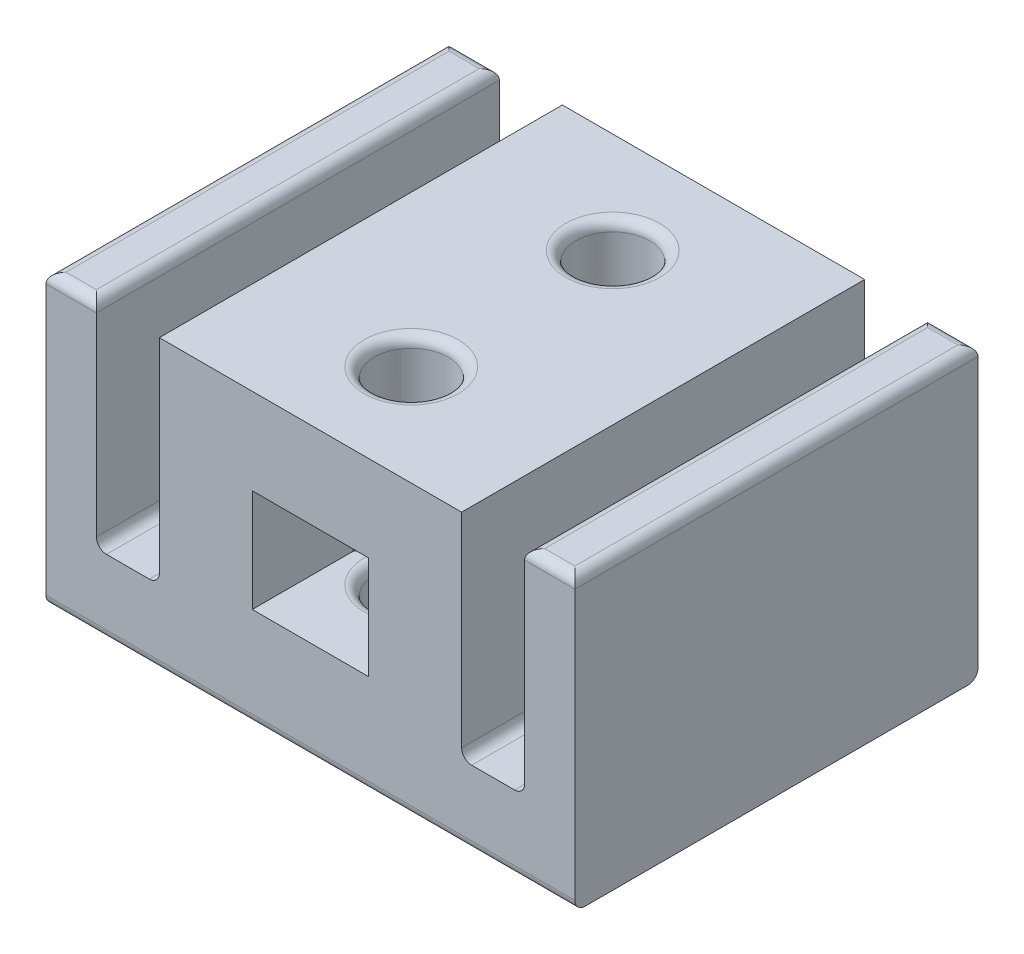
SolidWorks part; units mm, degrees
ref_plane "Front Plane" through (0, 0, 0) normal (0, 0, 1) x (1, 0, 0)
ref_plane "Top Plane" through (0, 0, 0) normal (0, 1, 0) x (1, 0, 0)
ref_plane "Right Plane" through (0, 0, 0) normal (1, 0, 0) x (0, 0, -1)
sketch "Sketch1" plane through (0, 0, 0) normal (0, 0, 1) x (1, 0, 0)
  line L0 (0, -18.7591) -> (0, 18.7591) construction
  line L1 (-12.7, 18.7591) -> (12.7, 18.7591) construction
  line L2 (12.7, 18.7591) -> (12.7, 6.8529) construction
  line L3 (-12.7, 18.7591) -> (-12.7, 6.8529) construction
  point P5 (0, 0)
  dimension "D1" = 12.7
  dimension "D2" = 11.9062
sketch "Sketch2" plane through (0, 0, 0) normal (0, 0, 1) x (1, 0, 0)
  line L0 (-12.7, 18.7591) -> (12.7, 18.7591) construction
  line L1 (-9.525, 18.7591) -> (9.525, 18.7591)
  line L2 (-9.525, 18.7591) -> (-9.525, 5.2654)
  line L3 (-9.525, 5.2654) -> (9.525, 5.2654) construction
  line L4 (9.525, 18.7591) -> (9.525, 5.2654)
  line L5 (12.7, 18.7591) -> (12.7, 6.8529) construction
  line L6 (9.525, 5.2654) -> (13.4938, 5.2654)
  line L7 (13.4938, 18.7591) -> (13.4938, 5.2654)
  line L8 (13.4938, 18.7591) -> (16.6688, 18.7591)
  line L9 (16.6688, 18.7591) -> (16.6688, 0.5029)
  line L10 (16.6688, 0.5029) -> (-16.6687, 0.5029)
  line L11 (-16.6687, 0.5029) -> (-16.6687, 18.7591)
  line L12 (-16.6687, 18.7591) -> (-13.4937, 18.7591)
  line L13 (-13.4937, 18.7591) -> (-13.4937, 5.2654)
  line L14 (-13.4937, 5.2654) -> (-9.525, 5.2654)
  line L15 (-12.7, 18.7591) -> (-12.7, 6.8529) construction
  point P20 (0, 0)
  point P23 (15.8316, 17.4334)
  dimension "D1" = 3.175
  dimension "D2" = 3.175
  dimension "D3" = 1.5875
  dimension "D4" = 0.7937
  dimension "D5" = 0.7937
  dimension "D6" = 3.175
  dimension "D7" = 4.7625
extrude "Boss-Extrude1" add sketch "Sketch2" along normal mid plane 25.4
sketch "Sketch4" plane through (0, 0.5029, 0) normal (0, -1, 0) x (1, 0, 0)
  line L0 (0, 0) -> (0, 6.35) construction
  circle A0 centre (0, 6.35) radius 2.3241
  circle A1 centre (0, -6.35) radius 2.3241
  point P6 (0, 0)
  dimension "D3" = 4.6482
  dimension "D1" = 6.35
  dimension "D2" = 6.35
extrude "Cut-Extrude1" cut sketch "Sketch4" against normal blind 19.05
sketch "Sketch5" plane through (0, 0.5029, 0) normal (0, -1, 0) x (1, 0, 0)
  line L0 (-3.6662, -6.35) -> (-3.6662, -14.1774)
  line L1 (1.8331, 9.525) -> (-1.8331, 9.525) construction
  line L2 (-1.8331, 9.525) -> (-3.6662, 6.35) construction
  line L3 (-3.6662, 6.35) -> (-1.8331, 3.175)
  line L4 (-1.8331, 3.175) -> (1.8331, 3.175)
  line L5 (1.8331, 3.175) -> (3.6662, 6.35)
  line L6 (3.6662, 6.35) -> (1.8331, 9.525) construction
  line L7 (3.6662, -6.35) -> (1.8331, -3.175)
  line L8 (1.8331, -3.175) -> (-1.8331, -3.175)
  line L9 (-1.8331, -3.175) -> (-3.6662, -6.35)
  line L10 (-3.6662, -6.35) -> (-1.8331, -9.525) construction
  line L11 (-1.8331, -9.525) -> (1.8331, -9.525) construction
  line L12 (1.8331, -9.525) -> (3.6662, -6.35) construction
  line L13 (-3.6662, -14.1774) -> (3.6662, -14.1774)
  line L14 (3.6662, -14.1774) -> (3.6662, -6.35)
  line L15 (3.6662, 6.35) -> (3.6662, 14.5068)
  line L16 (3.6662, 14.5068) -> (-3.6662, 14.5068)
  line L17 (-3.6662, 14.5068) -> (-3.6662, 6.35)
  circle A0 centre (0, 6.35) radius 3.175 construction
  circle A1 centre (0, -6.35) radius 3.175 construction
  dimension "D1" = 6.35
extrude "Cut-Extrude2" cut sketch "Sketch5" against normal blind 6.477 from offset 6.35 offset against normal yes
fillet "Fillet1" radius 0.635 22 edges at (2.3241, 0.5029, -6.35) (2.3241, 6.8529, -6.35) (2.3241, 0.5029, 6.35) (2.3241, 6.8529, 6.35) (2.3241, 13.3299, 6.35) (0, 18.7591, 4.0259) (2.3241, 13.3299, -6.35) (0, 18.7591, -8.6741) (16.6688, 18.7591, 0) (15.0813, 18.7591, 12.7) (13.4938, 18.7591, 0) (15.0813, 18.7591, -12.7) (-13.4937, 18.7591, 0) (-15.0812, 18.7591, 12.7) (-16.6687, 18.7591, 0) (-15.0812, 18.7591, -12.7) (0, 0.5029, -12.7) (0, 0.5029, 12.7) (13.4938, 5.2654, 0) (9.525, 5.2654, 0) (-13.4937, 5.2654, 0) (-9.525, 5.2654, 0)
